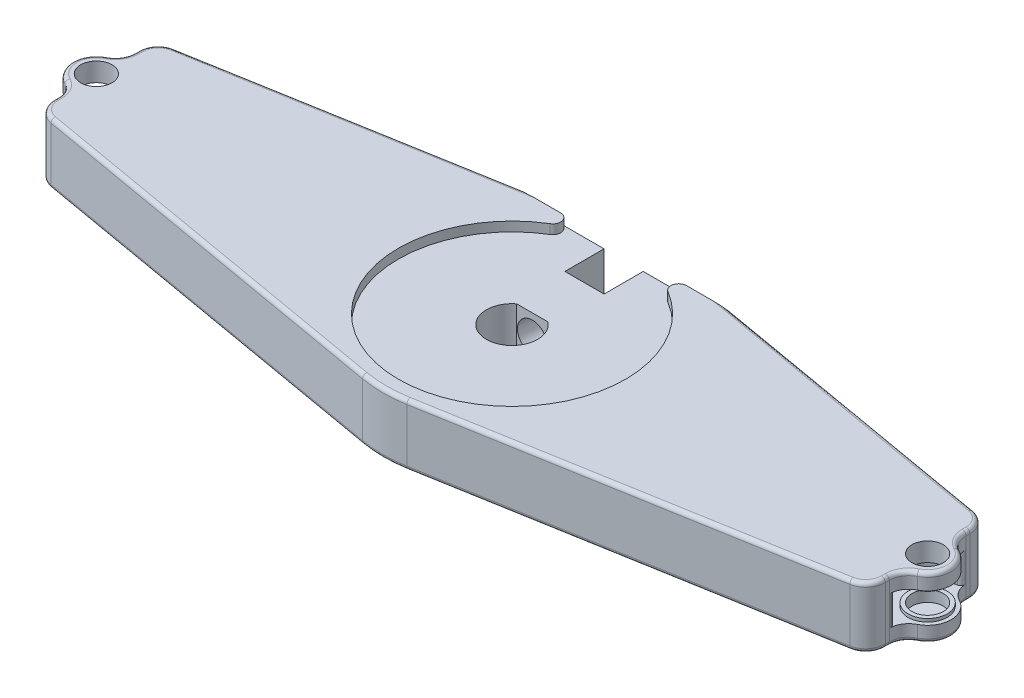
SolidWorks part; units mm, degrees
ref_plane "Front Plane" through (0, 0, 0) normal (0, 0, 1) x (1, 0, 0)
ref_plane "Top Plane" through (0, 0, 0) normal (0, 1, 0) x (1, 0, 0)
ref_plane "Right Plane" through (0, 0, 0) normal (1, 0, 0) x (0, 0, -1)
sketch "Sketch1" plane through (0, 0, 0) normal (0, 1, 0) x (1, 0, 0)
  line L0 (0, 0) -> (-57.07, 0) construction
  line L1 (-53.07, -5.398) -> (-53.07, -4.899)
  line L2 (-50.9992, 7.8609) -> (-2.8328, 16.255)
  line L3 (-50.9992, -7.8609) -> (-2.8328, -16.255)
  line L4 (-53.07, 4.899) -> (-53.07, 5.398)
  line L5 (0, -55) -> (0, 55) construction
  line L6 (53.07, -5.398) -> (53.07, -4.899)
  line L7 (50.9992, -7.8609) -> (2.8328, -16.255)
  line L8 (50.9992, 7.8609) -> (2.8328, 16.255)
  line L9 (53.07, 4.899) -> (53.07, 5.398)
  line L10 (0, -3.175) -> (0, 2.495) construction
  line L14 (-1.9636, 2.495) -> (1.9636, 2.495) construction
  line L15 (-1.9979, 2.595) -> (1.9979, 2.595)
  circle A0 centre (-53.07, 0) radius 4 construction
  arc A1 (-54.4336, 2.6722) -> (-54.4336, -2.6722) centre (-53.07, 0) ccw
  arc A3 (-2.8328, -16.255) -> (2.8328, -16.255) centre (0, 0) ccw
  arc A4 (54.4336, 2.6722) -> (54.4336, -2.6722) centre (53.07, 0) cw
  arc A5 (2.8328, -16.255) -> (-2.8328, -16.255) centre (0, 0) cw
  arc A6 (2.8328, 16.255) -> (-2.8328, 16.255) centre (0, 0) ccw
  arc A7 (-2.8328, 16.255) -> (2.8328, 16.255) centre (0, 0) cw
  arc A8 (50.9992, -7.8609) -> (53.07, -5.398) centre (50.57, -5.398) ccw
  arc A9 (54.4336, -2.6722) -> (53.07, -4.899) centre (55.57, -4.899) ccw
  arc A10 (54.4336, 2.6722) -> (53.07, 4.899) centre (55.57, 4.899) cw
  arc A11 (53.07, 5.398) -> (50.9992, 7.8609) centre (50.57, 5.398) ccw
  arc A12 (-53.07, 4.899) -> (-54.4336, 2.6722) centre (-55.57, 4.899) cw
  arc A13 (-54.4336, -2.6722) -> (-53.07, -4.899) centre (-55.57, -4.899) cw
  arc A14 (-53.07, -5.398) -> (-50.9992, -7.8609) centre (-50.57, -5.398) ccw
  arc A15 (-53.07, 5.398) -> (-50.9992, 7.8609) centre (-50.57, 5.398) cw
  arc A21 (-1.9636, 2.495) -> (1.9636, 2.495) centre (0, 0) ccw construction
  arc A22 (-1.9979, 2.595) -> (1.9979, 2.595) centre (0, 0) ccw
  point P11 (-53.07, 0)
  point P24 (53.07, -7.5)
  point P27 (53.07, -3)
  point P30 (53.07, 3)
  point P33 (53.07, 7.5)
  point P36 (-53.07, 3)
  point P39 (-53.07, -3)
  point P42 (-53.07, -7.5)
  point P45 (-53.07, 7.5)
  point P51 (0, 2.495)
  dimension "D3" = 6
  dimension "D4" = 6.35
  dimension "D5" = 33
  dimension "D9" = 2.5
  dimension "D1" = 57.07
  dimension "D2" = 4
  dimension "D6" = 15
  dimension "D7" = 4.5
  dimension "D8" = 50.9944
  dimension "D10" = 5.67
  dimension "D11" = 0.1
extrude "Boss-Extrude1" add sketch "Sketch1" along normal blind 2
sketch "Sketch2" plane through (0, 2, 0) normal (0, 1, 0) x (1, 0, 0)
  circle A0 centre (-53.07, 0) radius 2.5
  circle A1 centre (53.07, 0) radius 2.5
  dimension "D1" = 5
extrude "Boss-Extrude2" add sketch "Sketch2" along normal blind 0.4
sketch "Sketch3" plane through (0, 2.4, 0) normal (0, 1, 0) x (1, 0, 0)
  circle A0 centre (-53.07, 0) radius 2
  circle A1 centre (53.07, 0) radius 2
  dimension "D1" = 4
extrude "Boss-Extrude3" add sketch "Sketch3" along normal blind 3
sketch "Sketch5" plane through (0, 5.4, 0) normal (0, 1, 0) x (1, 0, 0)
  circle A2 centre (-53.07, 0) radius 2.5
  circle A3 centre (-53.07, 0) radius 2.5
  circle A5 centre (53.07, 0) radius 2.5
  circle A6 centre (53.07, 0) radius 2.5
  dimension "D1" = 0
  dimension "D2" = 0
extrude "Boss-Extrude4" add sketch "Sketch5" along normal blind 0.4
sketch "Sketch4" plane through (0, 2, 0) normal (0, 1, 0) x (1, 0, 0)
  line L2 (1.9979, 2.595) -> (-1.9979, 2.595)
  line L5 (1.9979, 2.595) -> (-1.9979, 2.595)
  line L16 (-53.07, 5.398) -> (-53.07, 4.899)
  line L17 (-53.07, -4.899) -> (-53.07, -5.398)
  line L18 (-50.9992, -7.8609) -> (-2.8328, -16.255)
  line L19 (2.8328, -16.255) -> (50.9992, -7.8609)
  line L20 (53.07, -5.398) -> (53.07, -4.899)
  line L21 (53.07, 4.899) -> (53.07, 5.398)
  line L22 (50.9992, 7.8609) -> (2.8328, 16.255)
  line L23 (-2.8328, 16.255) -> (-50.9992, 7.8609)
  line L24 (-53.07, 5.398) -> (-53.07, 4.899)
  line L25 (-53.07, -4.899) -> (-53.07, -5.398)
  line L26 (-50.9992, -7.8609) -> (-2.8328, -16.255)
  line L27 (2.8328, -16.255) -> (50.9992, -7.8609)
  line L28 (53.07, -5.398) -> (53.07, -4.899)
  line L29 (53.07, 4.899) -> (53.07, 5.398)
  line L30 (50.9992, 7.8609) -> (2.8328, 16.255)
  line L31 (-2.8328, 16.255) -> (-50.9992, 7.8609)
  arc A0 (-52.6272, -4.2269) -> (-52.6272, 4.2269) centre (-53.07, 0) ccw
  arc A1 (52.6272, 4.2269) -> (52.6272, -4.2269) centre (53.07, 0) ccw
  arc A9 (-1.9979, 2.595) -> (1.9979, 2.595) centre (0, 0) ccw
  arc A10 (-1.9979, 2.595) -> (1.9979, 2.595) centre (0, 0) ccw
  arc A14 (-52.6272, 4.2269) -> (-53.0742, 4.7533) centre (-52.5751, 4.7241) cw
  arc A15 (-52.6272, -4.2269) -> (-53.0742, -4.7533) centre (-52.5751, -4.7241) ccw
  arc A16 (52.6272, -4.2269) -> (53.0742, -4.7533) centre (52.5751, -4.7241) cw
  arc A17 (53.0742, 4.7533) -> (52.6272, 4.2269) centre (52.5751, 4.7241) cw
  arc A18 (2.8328, 16.255) -> (-2.8328, 16.255) centre (0, 0) ccw
  arc A19 (2.8328, 16.255) -> (-2.8328, 16.255) centre (0, 0) ccw
  arc A26 (-50.9992, 7.8609) -> (-53.07, 5.398) centre (-50.57, 5.398) ccw
  arc A27 (-54.4336, 2.6722) -> (-53.07, 4.899) centre (-55.57, 4.899) ccw
  arc A28 (-54.4336, 2.6722) -> (-54.4336, -2.6722) centre (-53.07, 0) ccw
  arc A29 (-53.07, -4.899) -> (-54.4336, -2.6722) centre (-55.57, -4.899) ccw
  arc A30 (-53.07, -5.398) -> (-50.9992, -7.8609) centre (-50.57, -5.398) ccw
  arc A31 (-2.8328, -16.255) -> (2.8328, -16.255) centre (0, 0) ccw
  arc A32 (50.9992, -7.8609) -> (53.07, -5.398) centre (50.57, -5.398) ccw
  arc A33 (54.4336, -2.6722) -> (53.07, -4.899) centre (55.57, -4.899) ccw
  arc A34 (54.4336, -2.6722) -> (54.4336, 2.6722) centre (53.07, 0) ccw
  arc A35 (53.07, 4.899) -> (54.4336, 2.6722) centre (55.57, 4.899) ccw
  arc A36 (53.07, 5.398) -> (50.9992, 7.8609) centre (50.57, 5.398) ccw
  arc A38 (-50.9992, 7.8609) -> (-53.07, 5.398) centre (-50.57, 5.398) ccw
  arc A39 (-53.0742, 4.7533) -> (-53.07, 4.899) centre (-55.57, 4.899) ccw
  arc A41 (-53.07, -4.899) -> (-53.0742, -4.7533) centre (-55.57, -4.899) ccw
  arc A42 (-53.07, -5.398) -> (-50.9992, -7.8609) centre (-50.57, -5.398) ccw
  arc A43 (-2.8328, -16.255) -> (2.8328, -16.255) centre (0, 0) ccw
  arc A44 (50.9992, -7.8609) -> (53.07, -5.398) centre (50.57, -5.398) ccw
  arc A45 (53.0742, -4.7533) -> (53.07, -4.899) centre (55.57, -4.899) ccw
  arc A47 (53.07, 4.899) -> (53.0742, 4.7533) centre (55.57, 4.899) ccw
  arc A48 (53.07, 5.398) -> (50.9992, 7.8609) centre (50.57, 5.398) ccw
  dimension "D1" = 8.5
  dimension "D2" = 0
  dimension "D3" = 0.5
  dimension "D4" = 0
extrude "Boss-Extrude5" add sketch "Sketch4" along normal up to surface (3.8 mm away) up to face at (-53.07, 5.8, 2.5)
sketch "Sketch6" plane through (0, 5.8, 0) normal (0, 1, 0) x (1, 0, 0)
  line L2 (1.9979, 2.595) -> (-1.9979, 2.595)
  line L5 (1.9979, 2.595) -> (-1.9979, 2.595)
  line L16 (-2.8328, 16.255) -> (-50.9992, 7.8609)
  line L17 (50.9992, 7.8609) -> (2.8328, 16.255)
  line L18 (53.07, 4.899) -> (53.07, 5.398)
  line L19 (53.07, -5.398) -> (53.07, -4.899)
  line L20 (2.8328, -16.255) -> (50.9992, -7.8609)
  line L21 (-50.9992, -7.8609) -> (-2.8328, -16.255)
  line L22 (-53.07, -4.899) -> (-53.07, -5.398)
  line L23 (-53.07, 5.398) -> (-53.07, 4.899)
  line L24 (-2.8328, 16.255) -> (-50.9992, 7.8609)
  line L25 (50.9992, 7.8609) -> (2.8328, 16.255)
  line L26 (53.07, 4.899) -> (53.07, 5.398)
  line L27 (53.07, -5.398) -> (53.07, -4.899)
  line L28 (2.8328, -16.255) -> (50.9992, -7.8609)
  line L29 (-50.9992, -7.8609) -> (-2.8328, -16.255)
  line L30 (-53.07, -4.899) -> (-53.07, -5.398)
  line L31 (-53.07, 5.398) -> (-53.07, 4.899)
  arc A6 (-1.9979, 2.595) -> (1.9979, 2.595) centre (0, 0) ccw
  arc A7 (-1.9979, 2.595) -> (1.9979, 2.595) centre (0, 0) ccw
  arc A14 (2.8328, 16.255) -> (-2.8328, 16.255) centre (0, 0) ccw
  arc A15 (2.8328, 16.255) -> (-2.8328, 16.255) centre (0, 0) ccw
  arc A24 (-50.9992, 7.8609) -> (-53.07, 5.398) centre (-50.57, 5.398) ccw
  arc A26 (53.07, 5.398) -> (50.9992, 7.8609) centre (50.57, 5.398) ccw
  arc A27 (53.07, 4.899) -> (54.4336, 2.6722) centre (55.57, 4.899) ccw
  arc A28 (54.4336, -2.6722) -> (54.4336, 2.6722) centre (53.07, 0) ccw
  arc A29 (54.4336, -2.6722) -> (53.07, -4.899) centre (55.57, -4.899) ccw
  arc A30 (50.9992, -7.8609) -> (53.07, -5.398) centre (50.57, -5.398) ccw
  arc A31 (-2.8328, -16.255) -> (2.8328, -16.255) centre (0, 0) ccw
  arc A32 (-53.07, -5.398) -> (-50.9992, -7.8609) centre (-50.57, -5.398) ccw
  arc A33 (-53.07, -4.899) -> (-54.4336, -2.6722) centre (-55.57, -4.899) ccw
  arc A34 (-54.4336, 2.6722) -> (-54.4336, -2.6722) centre (-53.07, 0) ccw
  arc A35 (-54.4336, 2.6722) -> (-53.07, 4.899) centre (-55.57, 4.899) ccw
  arc A36 (-50.9992, 7.8609) -> (-53.07, 5.398) centre (-50.57, 5.398) ccw
  arc A38 (53.07, 5.398) -> (50.9992, 7.8609) centre (50.57, 5.398) ccw
  arc A39 (53.07, 4.899) -> (54.4336, 2.6722) centre (55.57, 4.899) ccw
  arc A40 (54.4336, -2.6722) -> (54.4336, 2.6722) centre (53.07, 0) ccw
  arc A41 (54.4336, -2.6722) -> (53.07, -4.899) centre (55.57, -4.899) ccw
  arc A42 (50.9992, -7.8609) -> (53.07, -5.398) centre (50.57, -5.398) ccw
  arc A43 (-2.8328, -16.255) -> (2.8328, -16.255) centre (0, 0) ccw
  arc A44 (-53.07, -5.398) -> (-50.9992, -7.8609) centre (-50.57, -5.398) ccw
  arc A45 (-53.07, -4.899) -> (-54.4336, -2.6722) centre (-55.57, -4.899) ccw
  arc A46 (-54.4336, 2.6722) -> (-54.4336, -2.6722) centre (-53.07, 0) ccw
  arc A47 (-54.4336, 2.6722) -> (-53.07, 4.899) centre (-55.57, 4.899) ccw
  dimension "D1" = 0
  dimension "D2" = 0
extrude "Boss-Extrude6" add sketch "Sketch6" along normal blind 2
sketch "Sketch7" plane through (0, 0, 0) normal (0, -1, 0) x (1, 0, 0)
  line L9 (-2.8328, -16.255) -> (2.8328, -16.255) construction
  line L10 (-14.309, -14.255) -> (14.309, -14.255)
  line L11 (2.8328, -16.255) -> (50.9992, -7.8609)
  line L12 (-50.9992, -7.8609) -> (-2.8328, -16.255)
  line L13 (2.8328, -16.255) -> (14.309, -14.255)
  line L14 (-14.309, -14.255) -> (-2.8328, -16.255)
  arc A6 (-2.8328, -16.255) -> (2.8328, -16.255) centre (0, 0) ccw
  arc A7 (-2.8328, -16.255) -> (2.8328, -16.255) centre (0, 0) ccw
  dimension "D1" = 0
  dimension "D2" = 4
extrude "Cut-Extrude1" cut sketch "Sketch7" against normal through all
sketch "Sketch14" plane through (0, 0, 0) normal (0, 0, 1) x (1, 0, 0)
  line L0 (0, 7.8) -> (0, 0) construction
  line L1 (2.8328, 7.8) -> (-2.8328, 7.8) construction
  circle A0 centre (0, 3.9) radius 1.9
  dimension "D1" = 3.8
extrude "Cut-Extrude6" cut sketch "Sketch14" against normal through all
sketch "Sketch9" plane through (0, 7.8, 0) normal (0, 1, 0) x (1, 0, 0)
  circle A0 centre (0, 0) radius 14.5
  point P6 (0, 0)
  dimension "D1" = 29
extrude "Cut-Extrude3" cut sketch "Sketch9" against normal blind 1.2
fillet "Fillet1" radius 0.5 38 edges at (-32.6541, 0, -11.0579) (-52.4835, 0, -7.0069) (-53.07, 0, -5.1485) (-53.438, 0, -3.5934) (-56.07, 0, 0) (-53.438, 0, 3.5934) (-53.07, 0, 5.1485) (-52.4835, 0, 7.0069) (-26.916, 0, 12.0579) (0, 0, 16.5) (26.916, 0, 12.0579) (52.4835, 0, 7.0069) (53.07, 0, 5.1485) (53.438, 0, 3.5934) (56.07, 0, 0) (53.438, 0, -3.5934) (53.07, 0, -5.1485) (52.4835, 0, -7.0069) (-32.6541, 7.8, -11.0579) (-52.4835, 7.8, -7.0069) (-53.07, 7.8, -5.1485) (-53.438, 7.8, -3.5934) (-56.07, 7.8, 0) (-53.438, 7.8, 3.5934) (-53.07, 7.8, 5.1485) (-52.4835, 7.8, 7.0069) (-26.916, 7.8, 12.0579) (0, 7.8, 16.5) (26.916, 7.8, 12.0579) (52.4835, 7.8, 7.0069) (53.07, 7.8, 5.1485) (53.438, 7.8, 3.5934) (56.07, 7.8, 0) (53.438, 7.8, -3.5934) (53.07, 7.8, -5.1485) (52.4835, 7.8, -7.0069) (32.6541, 0, -11.0579) (32.6541, 7.8, -11.0579)
sketch "Sketch15" plane through (0, 0, -14.255) normal (0, 0, -1) x (-1, 0, 0)
  line L0 (-2.5, 6.6) -> (-2.5, 0)
  line L1 (14.5, 6.6) -> (-14.5, 6.6) construction
  line L2 (-11.3967, 0) -> (11.3967, 0) construction
  line L3 (-2.5, 0) -> (2.5, 0)
  line L4 (2.5, 0) -> (2.5, 6.6)
  line L5 (-2.6542, 6.6) -> (2.6542, 6.6) construction
  line L6 (2.5, 6.6) -> (-2.5, 6.6)
  point P6 (0, 6.6)
  dimension "D1" = 5
extrude "Cut-Extrude7" cut sketch "Sketch15" against normal blind 5
sketch "Sketch12" plane through (0, 0, 0) normal (0, -1, 0) x (1, 0, 0)
  circle A2 centre (-53.07, 0) radius 2
  circle A3 centre (-53.07, 0) radius 2
  circle A5 centre (53.07, 0) radius 2
  circle A6 centre (53.07, 0) radius 2
  dimension "D1" = 0
  dimension "D2" = 0
extrude "Cut-Extrude5" cut sketch "Sketch12" against normal through all from offset 1 offset against normal yes
fillet "Fillet4" radius 1 2 edges at (-2.6542, 7.2, -14.255) (2.6542, 7.2, -14.255)
